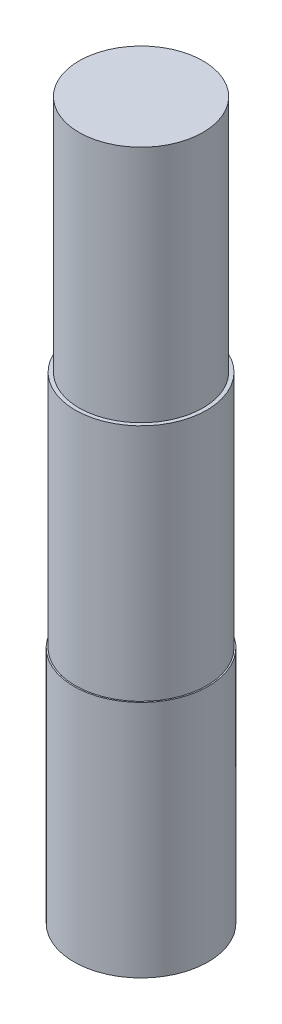
SolidWorks part; units mm, degrees
material "PUR"
ref_plane "Z" through (0, 0, 0) normal (0, 0, 1) x (1, 0, 0)
ref_plane "Y" through (0, 0, 0) normal (0, 1, 0) x (1, 0, 0)
ref_plane "X" through (0, 0, 0) normal (1, 0, 0) x (0, 0, -1)
sketch "Sketch1" plane through (0, 0, 0) normal (0, 1, 0) x (1, 0, 0)
  circle A0 centre (0, 0) radius 4.7625
  dimension "D1" = 9.525
extrude "Boss-Extrude1" add sketch "Sketch1" along normal blind 38.1
sketch "Sketch2" plane through (0, 38.1, 0) normal (0, 1, 0) x (1, 0, 0)
  circle A0 centre (0, 0) radius 3.3
  circle A1 centre (0, 0) radius 5.8325
  dimension "D1" = 6.6
extrude "Cut-Extrude1" cut sketch "Sketch2" against normal blind 12.7
sketch "Sketch3" plane through (0, 25.4, 0) normal (0, 1, 0) x (1, 0, 0)
  circle A0 centre (0, 0) radius 3.5
  circle A1 centre (0, 0) radius 5.3466
  dimension "D1" = 7
extrude "Cut-Extrude2" cut sketch "Sketch3" against normal blind 12.7
sketch "Sketch4" plane through (0, 0, 0) normal (0, -1, 0) x (1, 0, 0)
  circle A0 centre (0, 0) radius 3.5719
  circle A1 centre (0, 0) radius 4.9176
  dimension "D1" = 7.1437
extrude "Cut-Extrude3" cut sketch "Sketch4" against normal blind 12.7
